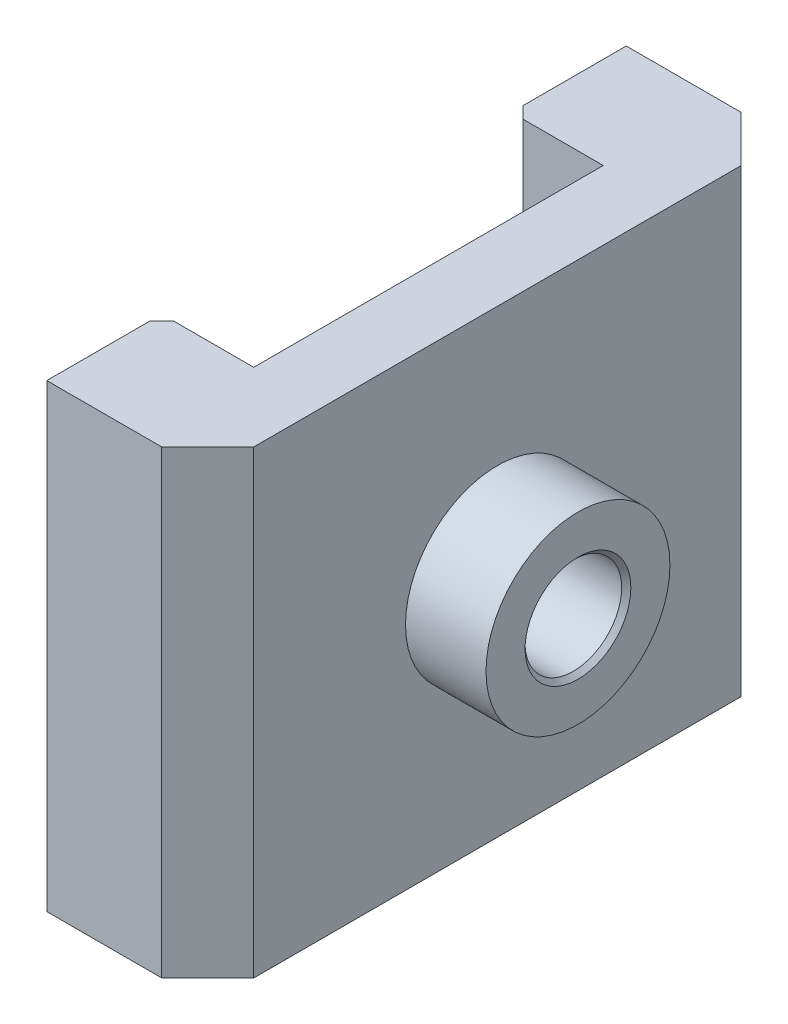
SolidWorks part; units mm, degrees
material "PLA"
ref_plane "前视基准面" through (0, 0, 0) normal (0, 0, 1) x (1, 0, 0)
ref_plane "上视基准面" through (0, 0, 0) normal (0, 1, 0) x (1, 0, 0)
ref_plane "右视基准面" through (0, 0, 0) normal (1, 0, 0) x (0, 0, -1)
sketch "草图1" plane through (0, 0, 0) normal (0, 1, 0) x (1, 0, 0)
  line L0 (-7, 12.6) -> (0, 12.6)
  line L1 (0, 12.6) -> (0, -12.6)
  line L2 (0, -12.6) -> (-7, -12.6)
  line L3 (-7, -12.6) -> (-7, -7.6)
  line L4 (-7, -7.6) -> (-3, -7.6)
  line L5 (-3, -7.6) -> (-3, 7.6)
  line L6 (-3, 7.6) -> (-7, 7.6)
  line L7 (-7, 7.6) -> (-7, 12.6)
  dimension "D1" = 15.2
  dimension "D2" = 5
  dimension "D3" = 3
  dimension "D4" = 4
extrude "凸台-拉伸1" add sketch "草图1" along normal blind 20
chamfer "倒角1" distance 2 angle 45 2 edges at (0, 10, -12.6) (0, 10, 12.6)
sketch "草图2" plane through (0, 0, 0) normal (1, 0, 0) x (0, 0, -1)
  line L0 (-12.6, 0) -> (-12.6, 20) construction
  circle A0 centre (0, 10) radius 4
  point P7 (-12.6, 10)
  dimension "D1" = 8
extrude "凸台-拉伸2" add sketch "草图2" along normal blind 3.5
sketch "草图3" plane through (3.5, 0, 0) normal (1, 0, 0) x (0, 0, -1)
  circle A0 centre (0, 10) radius 2.1
  dimension "D1" = 4.2
extrude "切除-拉伸1" cut sketch "草图3" against normal through all
chamfer "倒角2" distance 0.2 angle 45 1 edges at (3.5, 10, -2.1)
chamfer "倒角3" distance 0.5 angle 45 2 edges at (-7, 10, -7.6) (-7, 10, 7.6)
